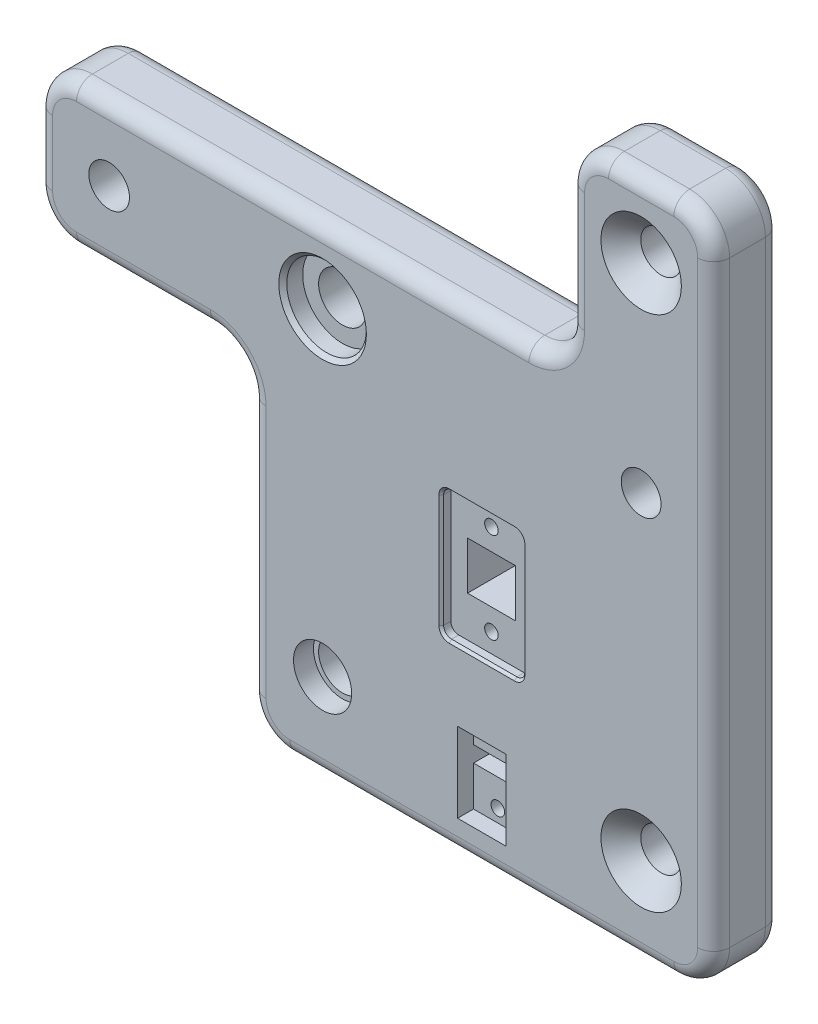
SolidWorks part; units mm, degrees
ref_plane "前视基准面" through (0, 0, 0) normal (0, 0, 1) x (1, 0, 0)
ref_plane "上视基准面" through (0, 0, 0) normal (0, 1, 0) x (1, 0, 0)
ref_plane "右视基准面" through (0, 0, 0) normal (1, 0, 0) x (0, 0, -1)
sketch "草图2" plane through (0, 0, 0) normal (0, 0, 1) x (1, 0, 0)
  line L1 (40, 0) -> (0, -40) construction
  line L2 (0, -40) -> (0, 0) construction
  line L3 (-10.9, 9.1) -> (25.9, 9.1)
  line L4 (-9.1, -14.1) -> (-9.1, -45.9)
  line L5 (-4.1, -50.9) -> (44.1, -50.9)
  line L6 (49.1, 9.1) -> (49.1, -45.9)
  line L7 (0, 0) -> (40, -40) construction
  line L8 (40, -40) -> (40, 0) construction
  line L9 (49.1, 9.1) -> (49.1, 29.1)
  line L10 (20, 17.2488) -> (20, -57.2488) construction
  line L11 (30.9, 14.1) -> (30.9, 29.1)
  line L12 (35.9, 34.1) -> (44.1, 34.1)
  line L13 (40, 0) -> (40, 34.6405) construction
  line L14 (-10.9, 9.1) -> (-30.9, 9.1)
  line L15 (-35.9, 4.1) -> (-35.9, -4.1)
  line L16 (-30.9, -9.1) -> (-14.1, -9.1)
  line L18 (17, -17) -> (23, -17)
  line L19 (17, -17) -> (17, -23)
  line L20 (17, -23) -> (23, -23)
  line L21 (23, -17) -> (23, -23)
  line L22 (17, -17) -> (23, -23) construction
  line L23 (17, -23) -> (23, -17) construction
  line L24 (16.95, -39.9) -> (23.05, -39.9)
  line L25 (16.95, -39.9) -> (16.95, -41.9)
  line L26 (16.95, -41.9) -> (23.05, -41.9)
  line L27 (23.05, -39.9) -> (23.05, -41.9)
  line L28 (16.95, -39.9) -> (23.05, -41.9) construction
  line L29 (16.95, -41.9) -> (23.05, -39.9) construction
  circle A0 centre (0, 0) radius 3
  circle A1 centre (40, 0) radius 2.5
  circle A2 centre (0, -40) radius 3
  circle A3 centre (40, -40) radius 2.55
  circle A4 centre (40, 25) radius 2.55
  circle A5 centre (-26.8, 0) radius 2.55
  arc A6 (49.1, 29.1) -> (44.1, 34.1) centre (44.1, 29.1) ccw
  arc A7 (30.9, 29.1) -> (35.9, 34.1) centre (35.9, 29.1) cw
  arc A8 (30.9, 14.1) -> (25.9, 9.1) centre (25.9, 14.1) cw
  arc A9 (44.1, -50.9) -> (49.1, -45.9) centre (44.1, -45.9) ccw
  arc A10 (-9.1, -45.9) -> (-4.1, -50.9) centre (-4.1, -45.9) ccw
  arc A11 (-14.1, -9.1) -> (-9.1, -14.1) centre (-14.1, -14.1) cw
  arc A12 (-35.9, -4.1) -> (-30.9, -9.1) centre (-30.9, -4.1) ccw
  arc A13 (-30.9, 9.1) -> (-35.9, 4.1) centre (-30.9, 4.1) ccw
  point P9 (20.9, -20.9)
  point P10 (20, -20)
  point P17 (20, -40.9)
  point P31 (49.1, 34.1)
  point P34 (30.9, 34.1)
  point P37 (30.9, 9.1)
  point P48 (-35.9, -9.1)
  point P51 (-35.9, 9.1)
  point P54 (20, -20)
  dimension "D1" = 6
  dimension "D2" = 5
  dimension "D4" = 6
  dimension "D6" = 5.1
  dimension "D17" = 5.1
  dimension "D18" = 5.1
  dimension "D19" = 5
  dimension "D3" = 40
  dimension "D5" = 40
  dimension "D7" = 6
  dimension "D8" = 60
  dimension "D9" = 25
  dimension "D10" = 9.1
  dimension "D11" = 9.1
  dimension "D12" = 9.1
  dimension "D13" = 25
  dimension "D14" = 18.2
  dimension "D15" = 18.2
  dimension "D16" = 9.1
  dimension "D20" = 6
  dimension "D21" = 6.1
  dimension "D22" = 2
  dimension "D23" = 10
  dimension "D24" = 40
  dimension "D25" = 9.1
  dimension "D26" = 9.1
extrude "凸台-拉伸2" add sketch "草图2" along normal blind 8.5
chamfer "倒角3" distance 2.5 angle 45 4 edges at (-24.25, 0, 0) (42.5, 0, 0) (42.55, 25, 8.5) (42.55, -40, 8.5)
fillet "圆角1" radius 3 1 edges at (20, -41.9, 0)
sketch "草图3" plane through (0, 0, 8.5) normal (0, 0, 1) x (1, 0, 0)
  line L0 (0, 0) -> (40, -40) construction
  line L6 (40, 0) -> (0, -40) construction
  line L7 (15.9, -11.9) -> (24.1, -11.9)
  line L8 (14.9, -12.9) -> (14.9, -27.1)
  line L9 (15.9, -28.1) -> (24.1, -28.1)
  line L10 (25.1, -12.9) -> (25.1, -27.1)
  line L11 (14.9, -11.9) -> (25.1, -28.1) construction
  line L12 (14.9, -28.1) -> (25.1, -11.9) construction
  arc A0 (24.1, -28.1) -> (25.1, -27.1) centre (24.1, -27.1) ccw
  arc A1 (14.9, -27.1) -> (15.9, -28.1) centre (15.9, -27.1) ccw
  arc A2 (24.1, -11.9) -> (25.1, -12.9) centre (24.1, -12.9) cw
  arc A3 (15.9, -11.9) -> (14.9, -12.9) centre (15.9, -12.9) ccw
  point P4 (20, -20)
  dimension "D3" = 1
  dimension "D1" = 16.2
  dimension "D2" = 10.2
extrude "切除-拉伸1" cut sketch "草图3" against normal blind 1.2
sketch "草图4" plane through (0, 0, 7.3) normal (0, 0, 1) x (1, 0, 0)
  line L0 (14.9, -20) -> (25.1, -20) construction
  line L1 (14.9, -12.9) -> (14.9, -27.1) construction
  line L2 (25.1, -27.1) -> (25.1, -12.9) construction
  line L4 (24.1, -11.9) -> (15.9, -11.9) construction
  line L5 (20, -11.9) -> (20, -28.1) construction
  line L6 (15.9, -28.1) -> (24.1, -28.1) construction
  circle A0 centre (20, -14.3) radius 0.85
  circle A1 centre (20, -25.7) radius 0.85
  dimension "D2" = 1.7
  dimension "D1" = 5.7
extrude "切除-拉伸2" cut sketch "草图4" against normal blind 5
sketch "草图5" plane through (0, 0, 0) normal (0, 0, -1) x (-1, 0, 0)
  line L0 (-40, 0) -> (0, -40) construction
  line L1 (0, -40) -> (0, 0) construction
  line L2 (0, 0) -> (-40, -40) construction
  line L4 (-27.1, -14.9) -> (-12.9, -14.9)
  line L5 (-28.1, -15.9) -> (-28.1, -24.1)
  line L6 (-27.1, -25.1) -> (-12.9, -25.1)
  line L7 (-11.9, -15.9) -> (-11.9, -24.1)
  line L8 (-28.1, -14.9) -> (-11.9, -25.1) construction
  line L9 (-28.1, -25.1) -> (-11.9, -14.9) construction
  arc A0 (-12.9, -14.9) -> (-11.9, -15.9) centre (-12.9, -15.9) cw
  arc A1 (-12.9, -25.1) -> (-11.9, -24.1) centre (-12.9, -24.1) ccw
  arc A2 (-28.1, -24.1) -> (-27.1, -25.1) centre (-27.1, -24.1) ccw
  arc A3 (-27.1, -14.9) -> (-28.1, -15.9) centre (-27.1, -15.9) ccw
  point P4 (-20, -20)
  dimension "D3" = 1
  dimension "D1" = 16.2
  dimension "D2" = 10.2
extrude "切除-拉伸3" cut sketch "草图5" against normal blind 1.2
sketch "草图6" plane through (0, 0, 1.2) normal (0, 0, -1) x (-1, 0, 0)
  line L0 (-20, -15.15) -> (-20, -24.85) construction
  line L1 (-28.1, -20) -> (-11.9, -20) construction
  line L2 (-28.1, -15.9) -> (-28.1, -24.1) construction
  line L3 (-11.9, -24.1) -> (-11.9, -15.9) construction
  arc A0 (-20.6021, -14.9) -> (-19.3979, -14.9) centre (-20, -14.3) ccw construction
  arc A1 (-19.3979, -25.1) -> (-20.6021, -25.1) centre (-20, -25.7) ccw construction
  circle A2 centre (-25.7, -20) radius 0.85
  circle A3 centre (-14.3, -20) radius 0.85
  dimension "D1" = 1.7
  dimension "D2" = 5.7
extrude "切除-拉伸4" cut sketch "草图6" against normal blind 5
fillet "圆角2" radius 2 32 edges at (-34.4355, 7.6355, 0) (-2.5, 9.1, 0) (29.4355, 10.5645, 0) (30.9, 21.6, 0) (32.3645, 32.6355, 0) (40, 34.1, 0) (47.6355, 32.6355, 0) (49.1, -8.4, 0) (47.6355, -49.4355, 0) (20, -50.9, 0) (-7.6355, -49.4355, 0) (-9.1, -30, 0) (-10.5645, -10.5645, 0) (-22.5, -9.1, 0) (-34.4355, -7.6355, 0) (29.4355, 10.5645, 8.5) (30.9, 21.6, 8.5) (32.3645, 32.6355, 8.5) (40, 34.1, 8.5) (47.6355, 32.6355, 8.5) (49.1, -8.4, 8.5) (47.6355, -49.4355, 8.5) (20, -50.9, 8.5) (-7.6355, -49.4355, 8.5) (-9.1, -30, 8.5) (-10.5645, -10.5645, 8.5) (-22.5, -9.1, 8.5) (-34.4355, -7.6355, 8.5) (-35.9, 0, 8.5) (-34.4355, 7.6355, 8.5) (-35.9, 0, 0) (-2.5, 9.1, 8.5)
sketch "草图7" plane through (0, 0, 8.5) normal (0, 0, -1) x (-1, 0, 0)
  line L0 (-16.95, -41.9) -> (-23.05, -41.9) construction
  line L1 (-23.05, -36.9) -> (-16.95, -36.9)
  line L2 (-23.05, -36.9) -> (-23.05, -46.9)
  line L3 (-23.05, -46.9) -> (-16.95, -46.9)
  line L4 (-16.95, -36.9) -> (-16.95, -46.9)
  line L5 (-23.05, -36.9) -> (-16.95, -46.9) construction
  line L6 (-23.05, -46.9) -> (-16.95, -36.9) construction
  point P0 (-20, -41.9)
  dimension "D1" = 10
extrude "切除-拉伸5" cut sketch "草图7" along normal blind 2
sketch "草图8" plane through (0, 0, 6.5) normal (0, 0, 1) x (1, 0, 0)
  line L0 (20, -36.9) -> (20, -46.9) construction
  line L1 (16.95, -36.9) -> (23.05, -36.9) construction
  line L2 (16.95, -46.9) -> (23.05, -46.9) construction
  circle A0 centre (20, -45.3) radius 0.85
  point P8 (0, 0)
  dimension "D1" = 1.7
extrude "切除-拉伸6" cut sketch "草图8" against normal blind 5
sketch "草图9" plane through (0, 0, 8.5) normal (0, 0, 1) x (1, 0, 0)
  circle A2 centre (0, -40) radius 3.65
  dimension "D1" = 7.3
extrude "切除-拉伸7" cut sketch "草图9" against normal blind 2.5
sketch "草图10" plane through (0, 0, 0) normal (0, 0, -1) x (-1, 0, 0)
  circle A0 centre (0, 0) radius 3.65
  dimension "D1" = 7.3
extrude "切除-拉伸8" cut sketch "草图10" against normal blind 2.5
sketch "草图11" plane through (0, 0, 0) normal (0, 0, -1) x (-1, 0, 0)
  circle A0 centre (0, -40) radius 5
  dimension "D1" = 10
extrude "切除-拉伸9" cut sketch "草图11" against normal blind 2.5
sketch "草图12" plane through (0, 0, 8.5) normal (0, 0, 1) x (1, 0, 0)
  circle A1 centre (0, 0) radius 5
  dimension "D1" = 10
extrude "切除-拉伸10" cut sketch "草图12" against normal blind 2.5
chamfer "倒角4" distance 0.5 angle 45 2 edges at (-5, -40, 0) (5, 0, 8.5)
chamfer "倒角5" distance 0.3 angle 45 16 edges at (11.9, -20, 0) (12.1929, -15.1929, 0) (12.1929, -24.8071, 0) (20, -14.9, 0) (20, -25.1, 0) (27.8071, -15.1929, 0) (27.8071, -24.8071, 0) (28.1, -20, 0) (14.9, -20, 8.5) (15.1929, -27.8071, 8.5) (15.1929, -12.1929, 8.5) (20, -28.1, 8.5) (20, -11.9, 8.5) (24.8071, -27.8071, 8.5) (24.8071, -12.1929, 8.5) (25.1, -20, 8.5)
